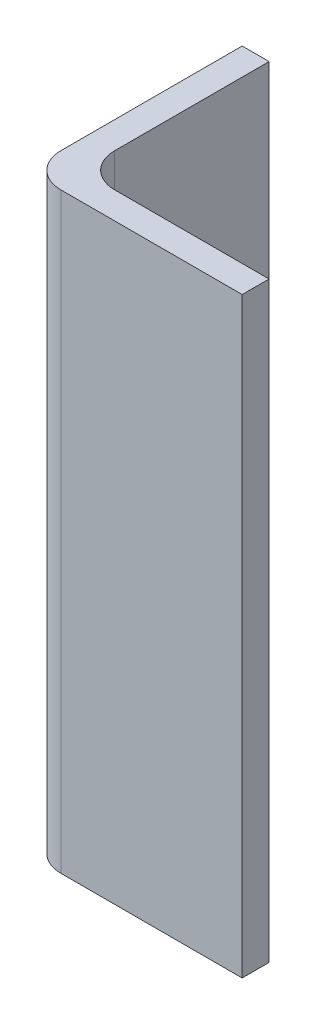
SolidWorks part; units mm, degrees
material "6061-T4 (SS)"
ref_plane "Front Plane" through (0, 0, 0) normal (0, 0, 1) x (1, 0, 0)
ref_plane "Top Plane" through (0, 0, 0) normal (0, 1, 0) x (1, 0, 0)
ref_plane "Right Plane" through (0, 0, 0) normal (1, 0, 0) x (0, 0, -1)
sketch "Sketch1" plane through (0, 0, 0) normal (0, 1, 0) x (1, 0, 0)
  line L1 (-7.9433, 9.7978) -> (-6.3533, 9.7978)
  line L2 (-7.9433, 9.7978) -> (-7.9433, -2.9022)
  line L3 (-7.9433, -2.9022) -> (-6.3533, -2.9022)
  line L4 (-6.3533, 9.7978) -> (-6.3533, -1.3147)
  line L5 (-6.3533, -2.9022) -> (4.7567, -2.9022)
  line L7 (-6.3533, -1.3147) -> (4.7567, -1.3147)
  line L8 (4.7567, -2.9022) -> (4.7567, -1.3147)
  point P7 (5.935, -2.2086)
  dimension "D1" = 1.5875
  dimension "D2" = 1.59
  dimension "D3" = 12.7
  dimension "D4" = 12.7
extrude "Boss-Extrude1" add sketch "Sketch1" along normal blind 34.925
fillet "Fillet1" radius 2 1 edges at (-6.3533, 17.4625, 1.3147)
fillet "Fillet2" radius 2 1 edges at (-7.9433, 17.4625, 2.9022)
